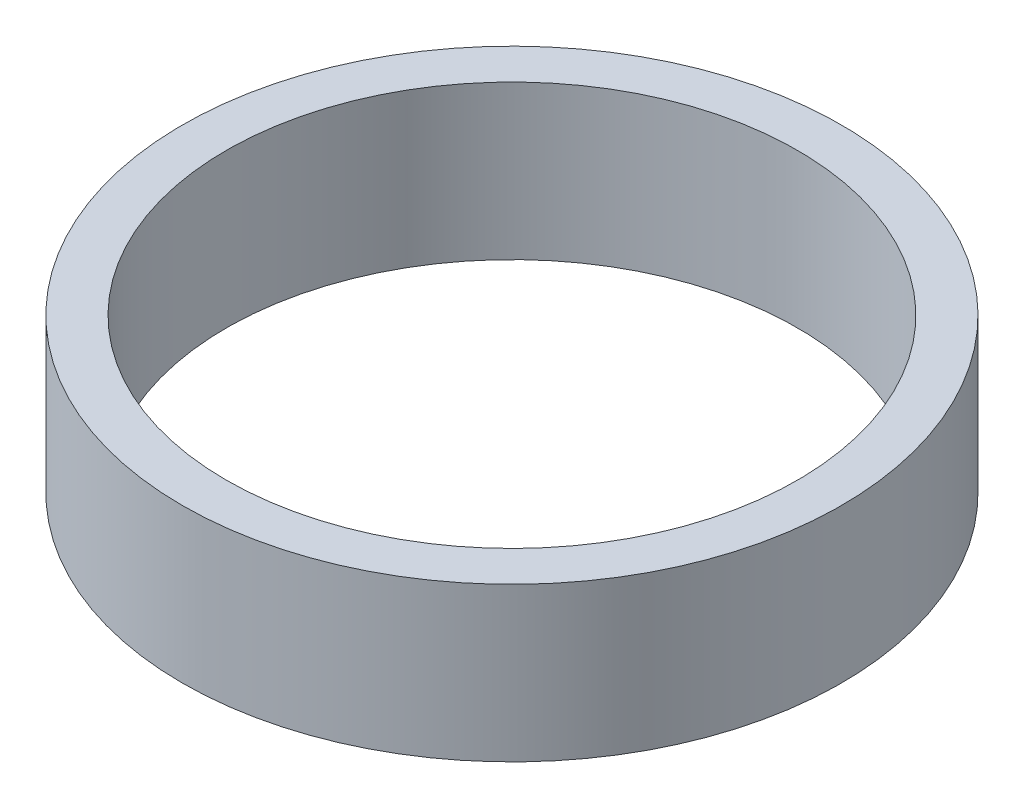
SolidWorks part; units mm, degrees
ref_plane "Ön Düzlem" through (0, 0, 0) normal (0, 0, 1) x (1, 0, 0)
ref_plane "Üst Düzlem" through (0, 0, 0) normal (0, 1, 0) x (1, 0, 0)
ref_plane "Sağ Düzlem" through (0, 0, 0) normal (1, 0, 0) x (0, 0, -1)
sketch "Çizim1" plane through (0, 0, 0) normal (0, 1, 0) x (1, 0, 0)
  circle A0 centre (0, 0) radius 150
  circle A1 centre (0, 0) radius 130
  dimension "D1" = 300
  dimension "D2" = 260
extrude "Yükseklik-Ekstrüzyon1" add sketch "Çizim1" along normal blind 70
